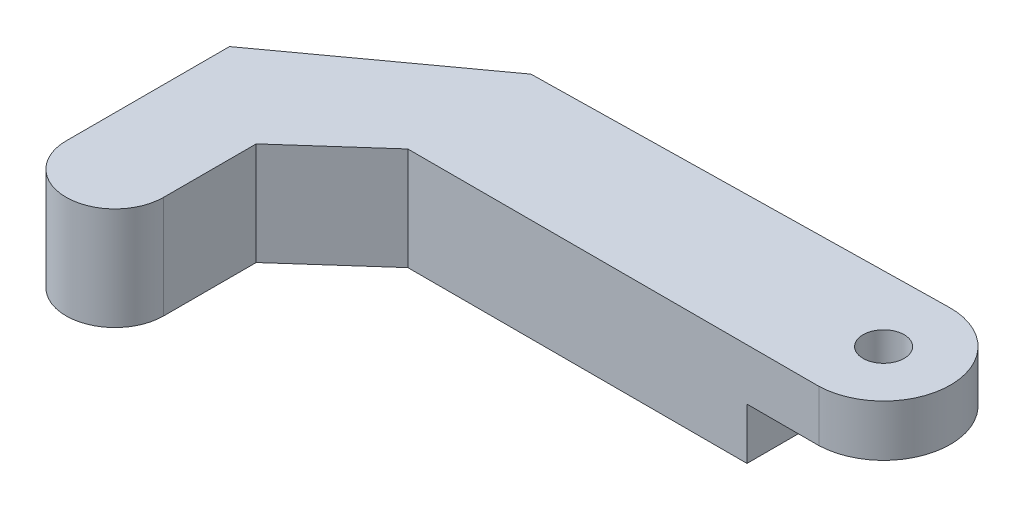
SolidWorks part; units mm, degrees
ref_plane "Alzado" through (0, 0, 0) normal (0, 0, 1) x (1, 0, 0)
ref_plane "Planta" through (0, 0, 0) normal (0, 1, 0) x (1, 0, 0)
ref_plane "Vista lateral" through (0, 0, 0) normal (1, 0, 0) x (0, 0, -1)
sketch "Croquis1" plane through (0, 0, 0) normal (0, 1, 0) x (1, 0, 0)
  line L0 (0.2047, -6.4968) -> (-39.7953, -6.4968)
  line L1 (-39.7953, -6.4968) -> (-47.6028, -13.4427)
  line L2 (-47.6028, -13.4427) -> (-47.6028, -22.4427)
  line L3 (-57.1028, -22.4427) -> (-57.1028, -6.5427)
  line L4 (-57.1028, -6.5427) -> (-40.1134, 5.8008)
  line L5 (-40.1134, 5.8008) -> (-0.1134, 6.499)
  circle A0 centre (0, 0) radius 2
  arc A1 (-47.6028, -22.4427) -> (-57.1028, -22.4427) centre (-52.3528, -22.4427) cw
  arc A2 (-0.1134, 6.499) -> (0.2047, -6.4968) centre (0, 0) cw
  dimension "D1" = 4
  dimension "D7" = 4.75
  dimension "D9" = 6.5
  dimension "D2" = 40
  dimension "D3" = 40
  dimension "D4" = 21
  dimension "D5" = 10.45
  dimension "D6" = 15.9
  dimension "D8" = 9
  dimension "D10" = 145
  dimension "D11" = 126
extrude "Saliente-Extruir1" add sketch "Croquis1" along normal blind 10
sketch "Croquis3" plane through (0, 0, 0) normal (0, -1, 0) x (1, 0, 0)
  line L0 (0.2047, 6.4968) -> (-6.7953, 6.4968)
  line L1 (-39.7953, 6.4968) -> (0.2047, 6.4968) construction
  line L2 (-6.7953, 6.4968) -> (-6.7953, -6.3824)
  line L3 (-0.1134, -6.499) -> (-40.1134, -5.8008) construction
  line L4 (-6.7953, -6.3824) -> (-0.1134, -6.499)
  circle A0 centre (0, 0) radius 2
  arc A1 (-0.1134, -6.499) -> (0.2047, 6.4968) centre (0, 0) ccw
  dimension "D1" = 4
  dimension "D2" = 7
extrude "Cortar-Extruir1" cut sketch "Croquis3" against normal blind 5
